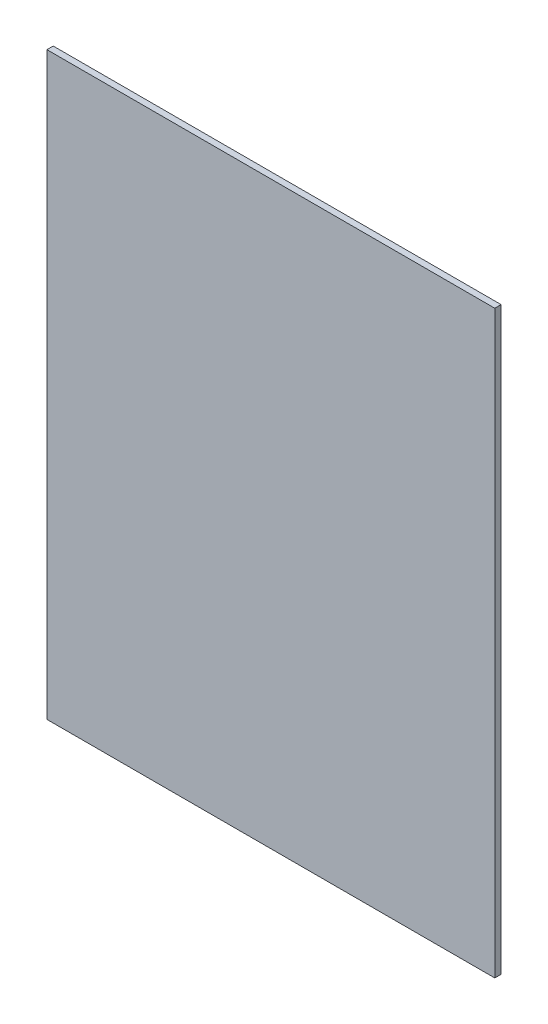
SolidWorks part; units mm, degrees
ref_plane "Front Plane" through (0, 0, 0) normal (0, 0, 1) x (1, 0, 0)
ref_plane "Top Plane" through (0, 0, 0) normal (0, 1, 0) x (1, 0, 0)
ref_plane "Right Plane" through (0, 0, 0) normal (1, 0, 0) x (0, 0, -1)
sketch "Sketch2" plane through (0, 0, 0) normal (0, 0, 1) x (1, 0, 0)
  line L1 (0, 0) -> (225.552, 0)
  line L2 (0, 0) -> (0, 292.1)
  line L3 (0, 292.1) -> (225.552, 292.1)
  line L4 (225.552, 0) -> (225.552, 292.1)
  dimension "D1" = 225.552
  dimension "D2" = 292.1
extrude "Boss-Extrude1" add sketch "Sketch2" along normal blind 3.175
